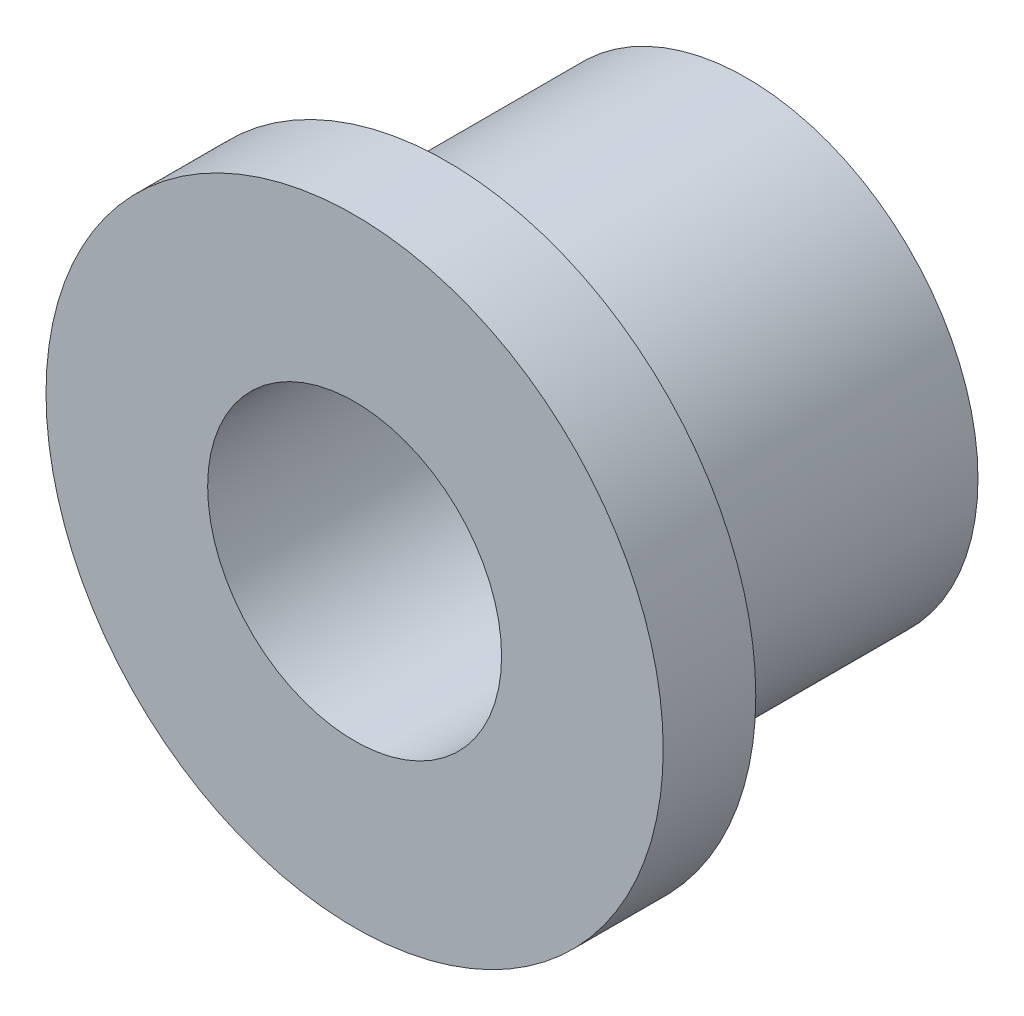
SolidWorks part; units mm, degrees
ref_plane "Front" through (0, 0, 0) normal (0, 0, 1) x (1, 0, 0)
ref_plane "Top" through (0, 0, 0) normal (0, 1, 0) x (1, 0, 0)
ref_plane "Right" through (0, 0, 0) normal (1, 0, 0) x (0, 0, -1)
sketch "Sketch1" plane through (0, 0, 0) normal (0, 0, 1) x (1, 0, 0)
  circle A0 centre (0, 0) radius 7.5
  dimension "D1" = 15
extrude "Boss-Extrude1" add sketch "Sketch1" along normal mid plane 12.7
sketch "Sketch2" plane through (0, 0, 6.35) normal (0, 0, 1) x (1, 0, 0)
  circle A0 centre (0, 0) radius 4.7625
  dimension "D1" = 9.525
extrude "Cut-Extrude1" cut sketch "Sketch2" against normal up to surface (12.7 mm away) up to face at (7.5, 0, -6.35)
sketch "Sketch3" plane through (0, 0, 6.35) normal (0, 0, 1) x (1, 0, 0)
  circle A0 centre (0, 0) radius 4.7625
  circle A1 centre (0, 0) radius 10
  dimension "D1" = 9.525
  dimension "D2" = 20
extrude "Boss-Extrude2" add sketch "Sketch3" against normal blind 3
